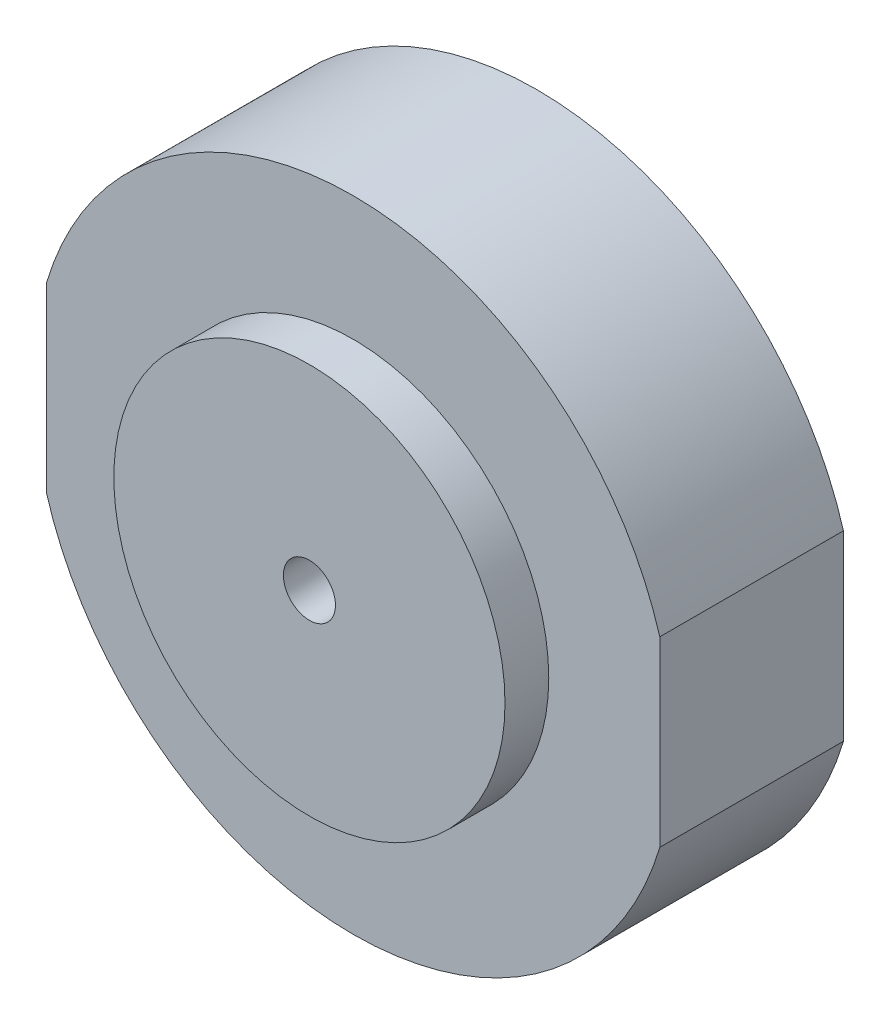
SolidWorks part; units mm, degrees
ref_plane "Front Plane" through (0, 0, 0) normal (0, 0, 1) x (1, 0, 0)
ref_plane "Top Plane" through (0, 0, 0) normal (0, 1, 0) x (1, 0, 0)
ref_plane "Right Plane" through (0, 0, 0) normal (1, 0, 0) x (0, 0, -1)
sketch "Sketch1" plane through (0, 0, 0) normal (0, 0, 1) x (1, 0, 0)
  circle A0 centre (0, 0) radius 48.25
extrude "Boss-Extrude1" add sketch "Sketch1" against normal blind 27.7 contours A0
sketch "Sketch2" plane through (0, 0, 0) normal (0, 0, 1) x (1, 0, 0)
  circle A0 centre (0, 0) radius 29.5
extrude "Boss-Extrude2" add sketch "Sketch2" along normal blind 6.6 contours A0
sketch "Sketch3" plane through (0, 0, -27.7) normal (0, 0, -1) x (-1, 0, 0)
  circle A0 centre (0, 0) radius 29
extrude "Boss-Extrude3" add sketch "Sketch3" along normal blind 8 contours A0
sketch "Sketch4" plane through (0, 0, 6.6) normal (0, 0, 1) x (1, 0, 0)
  circle A0 centre (0, 0) radius 3.9249
extrude "Cut-Extrude1" cut sketch "Sketch4" against normal blind 8 contours A0
sketch "Sketch6" plane through (0, 0, 0) normal (0, 0, 1) x (1, 0, 0)
  line L1 (-60.0636, 33.6707) -> (-46.25, 33.6707)
  line L2 (-60.0636, 33.6707) -> (-60.0636, -31.7938)
  line L3 (-60.0636, -31.7938) -> (-46.25, -31.7938)
  line L4 (-46.25, 33.6707) -> (-46.25, -31.7938)
  line L5 (46.25, 38.1751) -> (65.9194, 38.1751)
  line L6 (46.25, 38.1751) -> (46.25, -38.5505)
  line L7 (46.25, -38.5505) -> (65.9194, -38.5505)
  line L8 (65.9194, 38.1751) -> (65.9194, -38.5505)
  circle A0 centre (0, 0) radius 3.9249 construction
  dimension "D1" = 92.5
  dimension "D2" = 46.25
extrude "Cut-Extrude2" cut sketch "Sketch6" against normal blind 39
